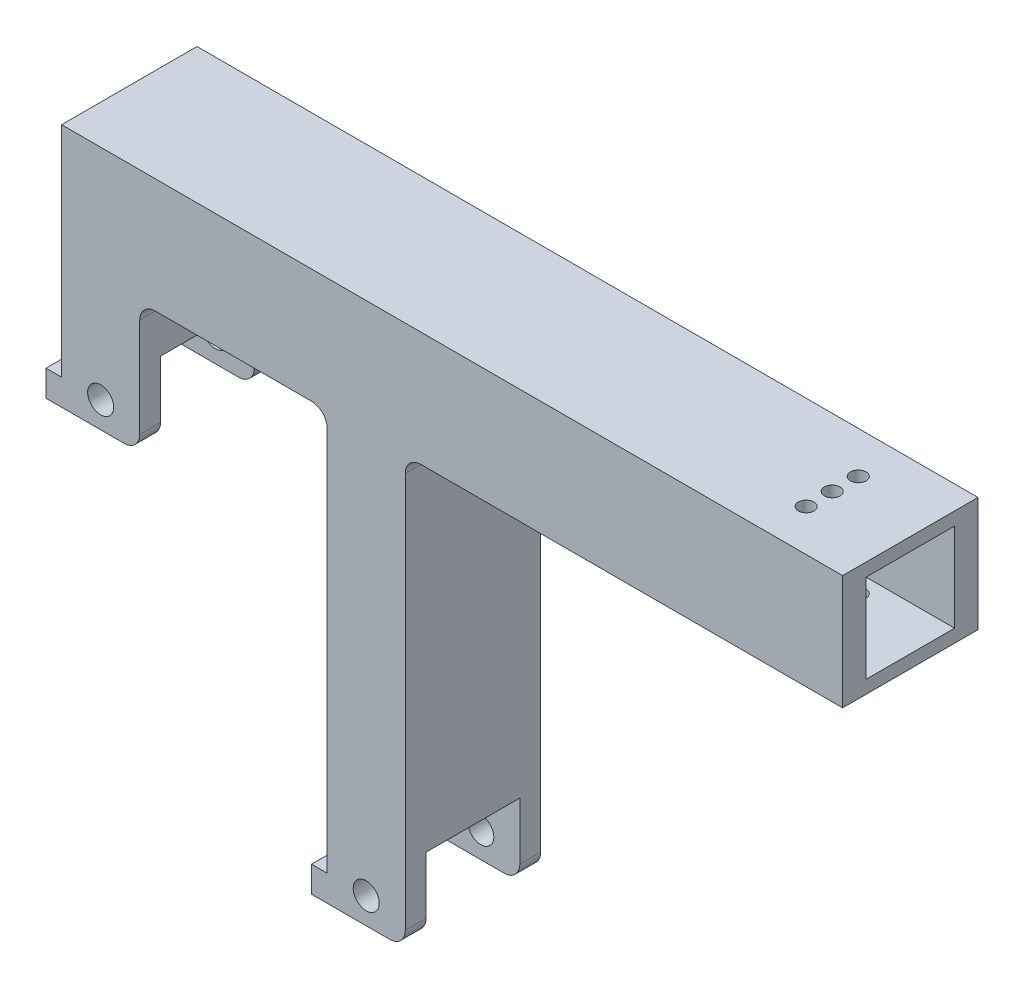
SolidWorks part; units mm, degrees
ref_plane "前视基准面" through (0, 0, 0) normal (0, 0, 1) x (1, 0, 0)
ref_plane "上视基准面" through (0, 0, 0) normal (0, 1, 0) x (1, 0, 0)
ref_plane "右视基准面" through (0, 0, 0) normal (1, 0, 0) x (0, 0, -1)
sketch "草图1" plane through (0, 0, 0) normal (0, 0, 1) x (1, 0, 0)
  line L0 (1.3385, 62.0602) -> (1.3385, 67.0602) construction
  line L1 (8.8385, 87.0602) -> (8.8385, 62.0602)
  line L5 (143.8385, 109.0602) -> (143.8385, 87.0602)
  line L7 (-6.1615, 87.0602) -> (-6.1615, 62.0602)
  line L9 (-6.1615, 87.0602) -> (-6.1615, 109.0602)
  line L12 (-6.1615, 62.0602) -> (8.8385, 62.0602)
  line L13 (-6.1615, 67.0602) -> (-9.1615, 67.0602)
  line L14 (-9.1615, 67.0602) -> (-9.1615, 62.0602)
  line L15 (-9.1615, 62.0602) -> (-6.1615, 62.0602)
  line L16 (-6.1615, 67.0602) -> (-6.1615, 62.0602)
  line L17 (8.8385, 87.0602) -> (44.8385, 87.0602)
  line L18 (44.8385, 87.0602) -> (44.8385, 5.0602)
  line L19 (44.8385, 5.0602) -> (59.8385, 5.0602)
  line L20 (59.8385, 5.0602) -> (59.8385, 87.0602)
  line L21 (59.8385, 87.0602) -> (143.8385, 87.0602)
  line L24 (-6.1615, 109.0602) -> (143.8385, 109.0602)
  line L25 (44.8385, 10.0602) -> (41.8385, 10.0602)
  line L26 (41.8385, 10.0602) -> (41.8385, 5.0602)
  line L27 (41.8385, 5.0602) -> (44.8385, 5.0602)
  line L28 (44.8385, 10.0602) -> (44.8385, 5.0602)
  line L29 (52.3385, 5.0602) -> (52.3385, 10.0602) construction
  circle A4 centre (1.3385, 67.0602) radius 2.5
  circle A10 centre (52.3385, 10.0602) radius 2.5
  point P13 (-14.3729, 38.9934)
  dimension "D3" = 57
  dimension "D4" = 36
  dimension "D8" = 5
  dimension "D10" = 5
  dimension "D7" = 5
  dimension "D2" = 150
  dimension "D5" = 25
  dimension "D11" = 3
  dimension "D14" = 15
  dimension "D15" = 22
extrude "凸台-拉伸2" add sketch "草图1" along normal blind 26
sketch "草图5" plane through (44.8385, 0, 0) normal (-1, 0, 0) x (0, 0, 1)
  line L1 (26, 5.0602) -> (0, 5.0602) construction
  line L2 (22, 5.0602) -> (4, 5.0602)
  line L5 (22, 19.0602) -> (22, 5.0602)
  line L6 (22, 19.0602) -> (4, 19.0602)
  line L7 (4, 19.0602) -> (4, 5.0602)
  line L8 (13, 5.0602) -> (13, 19.0602) construction
  dimension "D1" = 14
  dimension "D2" = 18
extrude "切除-拉伸3" cut sketch "草图5" against normal up to next
sketch "草图7" plane through (0, 109.0602, 0) normal (0, 1, 0) x (1, 0, 0)
  line L1 (143.8385, -26) -> (143.8385, 0) construction
  line L2 (79.1739, -13) -> (143.8385, -13) construction
  circle A0 centre (128.8374, -13) radius 1.5
  circle A2 centre (128.8374, -8) radius 1.5
  circle A3 centre (128.8374, -18) radius 1.5
  dimension "D1" = 3
  dimension "D3" = 5
  dimension "D2" = 15.0012
extrude "切除-拉伸5" cut sketch "草图7" against normal up to surface (22 mm away) and the other way through all up to face at (101.8385, 87.0602, 13)
sketch "草图8" plane through (143.8385, 0, 0) normal (1, 0, 0) x (0, 0, -1)
  line L0 (-26, 98.0602) -> (0, 98.0602) construction
  line L1 (-26, 109.0602) -> (-26, 87.0602) construction
  line L2 (0, 109.0602) -> (0, 87.0602) construction
  line L4 (-21.5, 89.5602) -> (-4.5, 89.5602)
  line L5 (-21.5, 89.5602) -> (-21.5, 106.5602)
  line L6 (-21.5, 106.5602) -> (-4.5, 106.5602)
  line L7 (-4.5, 89.5602) -> (-4.5, 106.5602)
  line L8 (-21.5, 89.5602) -> (-4.5, 106.5602) construction
  line L9 (-21.5, 106.5602) -> (-4.5, 89.5602) construction
  point P6 (-13, 98.0602)
  dimension "D1" = 17
  dimension "D2" = 17
extrude "切除-拉伸6" cut sketch "草图8" against normal through all
sketch "草图9" plane through (8.8385, 0, 0) normal (1, 0, 0) x (0, 0, -1)
  line L0 (-26, 62.0602) -> (0, 62.0602) construction
  line L1 (-26, 67.0602) -> (0, 67.0602) construction
  line L2 (-26, 62.0602) -> (0, 62.0602) construction
  line L3 (-26, 67.0602) -> (0, 67.0602) construction
  line L4 (-13, 62.0602) -> (-13, 76.0602) construction
  line L6 (-22, 62.0602) -> (-4, 62.0602)
  line L7 (-22, 62.0602) -> (-22, 76.0602)
  line L8 (-22, 76.0602) -> (-4, 76.0602)
  line L9 (-4, 62.0602) -> (-4, 76.0602)
  line L10 (-22, 62.0602) -> (-4, 76.0602) construction
  line L11 (-22, 76.0602) -> (-4, 62.0602) construction
  point P6 (-13, 69.0602)
  dimension "D1" = 18
  dimension "D2" = 14
extrude "切除-拉伸7" cut sketch "草图9" against normal up to surface (15 mm away) up to face at (-6.1615, 98.0602, 13)
fillet "圆角1" radius 3 2 edges at (8.8385, 87.0602, 13) (59.8385, 87.0602, 13)
fillet "圆角2" radius 3 1 edges at (44.8385, 87.0602, 13)
fillet "圆角3" radius 3 1 edges at (8.8385, 62.0602, 24)
fillet "圆角4" radius 3 3 edges at (59.8385, 5.0602, 2) (59.8385, 5.0602, 24) (8.8385, 62.0602, 2)
